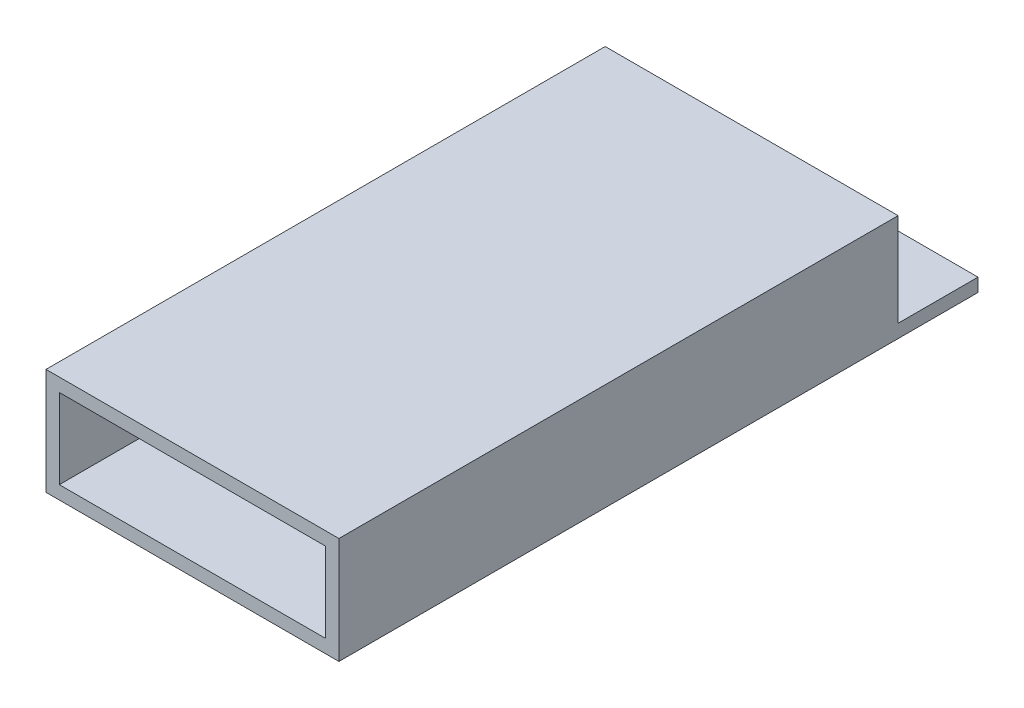
SolidWorks part; units mm, degrees
ref_plane "Front Plane" through (0, 0, 0) normal (0, 0, 1) x (1, 0, 0)
ref_plane "Top Plane" through (0, 0, 0) normal (0, 1, 0) x (1, 0, 0)
ref_plane "Right Plane" through (0, 0, 0) normal (1, 0, 0) x (0, 0, -1)
sketch "Sketch1" plane through (0, 0, 0) normal (0, 0, 1) x (1, 0, 0)
  line L1 (-110, -40) -> (110, -40)
  line L2 (-110, -40) -> (-110, 40)
  line L3 (-110, 40) -> (110, 40)
  line L4 (110, -40) -> (110, 40)
  line L5 (-110, -40) -> (110, 40) construction
  line L6 (-110, 40) -> (110, -40) construction
  line L7 (-100, -30) -> (100, -30)
  line L8 (-100, -30) -> (-100, 30)
  line L9 (-100, 30) -> (100, 30)
  line L10 (100, -30) -> (100, 30)
  line L11 (-100, -30) -> (100, 30) construction
  line L12 (-100, 30) -> (100, -30) construction
  point P0 (0, 0)
  point P7 (0, 0)
  dimension "D1" = 80
  dimension "D2" = 220
  dimension "D3" = 200
  dimension "D4" = 60
extrude "Boss-Extrude1" add sketch "Sketch1" along normal blind 420
sketch "Sketch3" plane through (0, 0, 0) normal (0, 0, -1) x (-1, 0, 0)
  line L0 (110, 40) -> (110, -40) construction
  line L1 (-110, -40) -> (110, -40)
  line L2 (-110, -40) -> (-110, -30)
  line L3 (-110, -30) -> (110, -30)
  line L4 (110, -40) -> (110, -30)
extrude "Boss-Extrude3" add sketch "Sketch3" along normal blind 60
